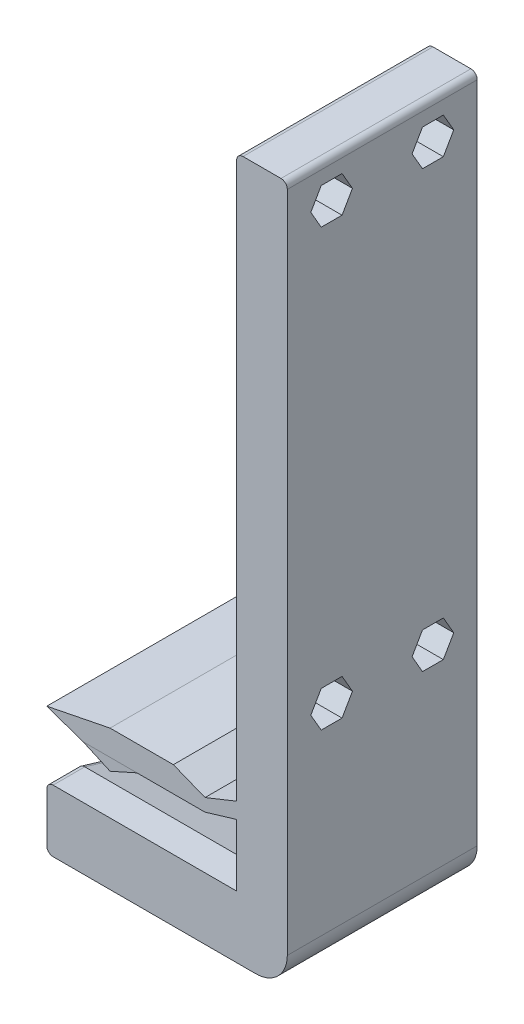
SolidWorks part; units mm, degrees
ref_plane "Front Plane" through (0, 0, 0) normal (0, 0, 1) x (1, 0, 0)
ref_plane "Top Plane" through (0, 0, 0) normal (0, 1, 0) x (1, 0, 0)
ref_plane "Right Plane" through (0, 0, 0) normal (1, 0, 0) x (0, 0, -1)
sketch "Sketch1" plane through (0, 0, 0) normal (0, 0, 1) x (1, 0, 0)
  line L0 (-13.25, 40.4) -> (-13.25, -40.4)
  line L1 (-13.25, 25.4) -> (13.25, 25.4)
  line L2 (-13.25, 25.4) -> (-13.25, -25.4)
  line L3 (-13.25, -25.4) -> (13.25, -25.4)
  line L4 (13.25, 25.4) -> (13.25, -25.4)
  line L5 (-13.25, 25.4) -> (13.25, -25.4) construction
  line L6 (-13.25, -25.4) -> (13.25, 25.4) construction
  line L7 (-13.25, 40.4) -> (-21.25, 40.4)
  line L8 (-21.25, 40.4) -> (-21.25, -40.4)
  line L9 (-21.25, -40.4) -> (-13.25, -40.4)
  point P0 (0, 0)
  point P9 (-13.25, 0)
  dimension "D1" = 26.5
  dimension "D2" = 50.8
  dimension "D3" = 15
  dimension "D4" = 8
extrude "Boss-Extrude1" add sketch "Sketch1" along normal blind 30 contours L8 L9 L0 L7
sketch "Sketch2" plane through (-13.25, 0, 0) normal (1, 0, 0) x (0, 0, -1)
  line L0 (-15, 40.4) -> (-15, -40.4) construction
  line L1 (-30, 40.4) -> (0, 40.4) construction
  line L2 (-30, -40.4) -> (0, -40.4) construction
  line L3 (0, 40.4) -> (0, -40.4) construction
  line L4 (-30, 25.4) -> (0, 25.4)
  line L5 (-30, 25.4) -> (-30, -25.4)
  line L6 (-30, -25.4) -> (0, -25.4)
  line L7 (0, 25.4) -> (0, -25.4)
  line L8 (-30, 25.4) -> (0, -25.4) construction
  line L9 (-30, -25.4) -> (0, 25.4) construction
  line L10 (-30, 40.4) -> (-30, -40.4) construction
  circle A0 centre (-7, 34.4) radius 1.65
  circle A1 centre (-23, 34.4) radius 1.65
  circle A2 centre (-23, -34.4) radius 1.65
  circle A3 centre (-7, -34.4) radius 1.65
  point P6 (-15, 0)
  dimension "D2" = 7
  dimension "D3" = 9
  dimension "D4" = 7
  dimension "D5" = 9
  dimension "D6" = 3.3
  dimension "D7" = 3.3
  dimension "D8" = 7
  dimension "D9" = 9
  dimension "D10" = 9
  dimension "D11" = 7
  dimension "D12" = 3.3
  dimension "D13" = 3.3
  dimension "D1" = 50.8
extrude "Cut-Extrude1" cut sketch "Sketch2" against normal blind 30 contours A1 | A0 | A2 | A3
sketch "Sketch3" plane through (-13.25, 0, 0) normal (1, 0, 0) x (0, 0, -1)
  line L0 (-30, -40.4) -> (0, -40.4) construction
  line L25 (-26.2909, 34.4) -> (-24.6454, 31.55)
  line L26 (-24.6454, 31.55) -> (-21.3546, 31.55)
  line L27 (-21.3546, 31.55) -> (-19.7091, 34.4)
  line L28 (-19.7091, 34.4) -> (-21.3546, 37.25)
  line L29 (-21.3546, 37.25) -> (-24.6454, 37.25)
  line L30 (-24.6454, 37.25) -> (-26.2909, 34.4)
  line L31 (-10.2909, 34.4) -> (-8.6454, 31.55)
  line L32 (-8.6454, 31.55) -> (-5.3546, 31.55)
  line L33 (-5.3546, 31.55) -> (-3.7091, 34.4)
  line L34 (-3.7091, 34.4) -> (-5.3546, 37.25)
  line L35 (-5.3546, 37.25) -> (-8.6454, 37.25)
  line L36 (-8.6454, 37.25) -> (-10.2909, 34.4)
  line L37 (-19.7091, -34.4) -> (-21.3546, -31.55)
  line L38 (-21.3546, -31.55) -> (-24.6454, -31.55)
  line L39 (-24.6454, -31.55) -> (-26.2909, -34.4)
  line L40 (-26.2909, -34.4) -> (-24.6454, -37.25)
  line L41 (-24.6454, -37.25) -> (-21.3546, -37.25)
  line L42 (-21.3546, -37.25) -> (-19.7091, -34.4)
  line L43 (-3.7091, -34.4) -> (-5.3546, -31.55)
  line L44 (-5.3546, -31.55) -> (-8.6454, -31.55)
  line L45 (-8.6454, -31.55) -> (-10.2909, -34.4)
  line L46 (-10.2909, -34.4) -> (-8.6454, -37.25)
  line L47 (-8.6454, -37.25) -> (-5.3546, -37.25)
  line L48 (-5.3546, -37.25) -> (-3.7091, -34.4)
  line L49 (-30, 40.4) -> (0, 40.4) construction
  circle A0 centre (-23, 34.4) radius 2.85 construction
  circle A1 centre (-7, 34.4) radius 2.85 construction
  circle A2 centre (-23, -34.4) radius 2.85 construction
  circle A3 centre (-7, -34.4) radius 2.85 construction
  point P28 (-23, -31.55)
  dimension "D1" = 5.7
  dimension "D2" = 5.7
  dimension "D3" = 5.7
  dimension "D4" = 5.7
  dimension "D5" = 180
  dimension "D6" = 0
  dimension "D7" = 0
  dimension "D8" = 0
extrude "Cut-Extrude3" cut sketch "Sketch3" along direction (1, 0, 0) on the side against the normal mid plane 10 contours L26 L27 L28 L29 L30 L25 | L32 L33 L34 L35 L36 L31 | L41 L42 L37 L38 L39 L40 | L44 L45 L46 L47 L48 L43
sketch "Sketch4" plane through (0, -40.4, 0) normal (0, -1, 0) x (1, 0, 0)
  line L1 (-21.25, 30) -> (-13.25, 30)
  line L2 (-21.25, 30) -> (-21.25, 0)
  line L3 (-21.25, 0) -> (-13.25, 0)
  line L4 (-13.25, 30) -> (-13.25, 0)
extrude "Boss-Extrude2" add sketch "Sketch4" along normal blind 30
sketch "Sketch5" plane through (-21.25, 0, 0) normal (-1, 0, 0) x (0, 0, 1)
  line L0 (30, 40.4) -> (30, -70.4) construction
  line L1 (0, -70.4) -> (30, -70.4)
  line L2 (0, -70.4) -> (0, -60.6)
  line L3 (0, -60.6) -> (30, -60.6)
  line L4 (30, -70.4) -> (30, -60.6)
  dimension "D1" = 9.8
extrude "Boss-Extrude3" add sketch "Sketch5" along normal blind 30
sketch "Sketch6" plane through (-21.25, 0, 0) normal (-1, 0, 0) x (0, 0, 1)
  line L0 (0, 40.4) -> (0, -60.6) construction
  line L1 (0, -48.3) -> (30, -48.3)
  line L2 (0, -48.3) -> (0, -52.3)
  line L3 (0, -52.3) -> (30, -52.3)
  line L4 (30, -48.3) -> (30, -52.3)
  line L5 (30, 40.4) -> (30, -60.6) construction
  line L6 (30, -60.6) -> (0, -60.6) construction
  dimension "D1" = 8.3
  dimension "D2" = 4
extrude "Boss-Extrude4" add sketch "Sketch6" along normal blind 30
sketch "Sketch8" plane through (0, 0, 0) normal (0, 0, -1) x (-1, 0, 0)
  line L0 (41.25, -52.3) -> (41.25, -54.2) construction
  line L1 (51.25, -52.3) -> (21.25, -52.3) construction
  line L2 (37, -52.3) -> (45.5, -52.3)
  line L3 (37, -52.3) -> (41.25, -54.2)
  line L4 (41.25, -54.2) -> (45.5, -52.3)
  line L5 (21.25, -52.3) -> (21.25, -60.6) construction
  point P7 (41.25, -52.3)
  dimension "D1" = 8.5
  dimension "D2" = 1.9
  dimension "D3" = 20
extrude "Boss-Extrude5" add sketch "Sketch8" against normal blind 30 separate body
sketch "Sketch9" plane through (0, 0, 0) normal (0, 0, -1) x (-1, 0, 0)
  line L0 (51.25, -52.3) -> (51.25, -50.3) construction
  line L1 (51.25, -48.3) -> (51.25, -52.3) construction
  line L2 (41.25, -54.2) -> (41.25, -48.3) construction
  line L3 (51.25, -48.3) -> (21.25, -48.3) construction
  line L4 (41.25, -48.3) -> (51.25, -50.3) construction
  line L5 (51.25, -50.3) -> (45.5, -52.3) construction
  line L6 (41.25, -48.3) -> (51.25, -50.3)
  line L7 (51.25, -50.3) -> (45.5, -52.3)
  line L8 (21.25, -48.3) -> (31.25, -48.3)
  line L9 (26.25, -48.3) -> (26.25, -50.3) construction
  line L10 (26.25, -50.3) -> (31.25, -48.3)
  line L11 (26.25, -50.3) -> (21.25, -48.3)
  line L12 (37, -52.3) -> (45.5, -52.3)
  line L13 (21.25, 40.4) -> (21.25, -48.3) construction
  line L14 (41.25, -48.3) -> (51.25, -48.3)
  line L15 (51.25, -48.3) -> (51.25, -50.3)
  line L16 (51.25, -52.3) -> (45.5, -52.3)
  line L17 (45.5, -52.3) -> (51.25, -52.3)
  line L18 (51.25, -50.3) -> (45.5, -52.3)
  line L19 (45.5, -52.3) -> (51.25, -52.3)
  line L20 (51.25, -52.3) -> (51.25, -50.3)
  line L21 (45.5, -52.3) -> (51.25, -50.3)
  point P16 (26.25, -48.3)
  line M14 (51.25, -52.3) -> (51.25, -48.3)
  line M15 (51.25, -48.3) -> (21.25, -48.3)
  dimension "D1" = 10
  dimension "D2" = 5
  dimension "D3" = 2
extrude "Cut-Extrude8" cut sketch "Sketch9" against normal blind 30 contours L6 M15 M14 | L11 L10 M15
sketch "Sketch10" plane through (-51.25, 0, 0) normal (-1, 0, 0) x (0, 0, 1)
  line L0 (5, -60.6) -> (25, -60.6)
  line L2 (30, -60.6) -> (0, -60.6) construction
  line L3 (15, -60.6) -> (15, -63.6) construction
  line L4 (5, -60.6) -> (15, -63.6)
  line L5 (15, -63.6) -> (25, -60.6)
  line L6 (0, -60.6) -> (0, -70.4) construction
  point P5 (7.2012, -60.4)
  point P6 (15, -60.6)
  dimension "D1" = 3
  dimension "D2" = 20
  dimension "D3" = 15
extrude "Cut-Extrude9" cut sketch "Sketch10" against normal blind 30
sketch "Sketch11" plane through (0, 0, 0) normal (0, 0, -1) x (-1, 0, 0)
  line L0 (21.25, -48.3) -> (21.25, -52.3) construction
  line L1 (26.25, -50.3) -> (26.25, -52.3) construction
  line L3 (51.25, -52.3) -> (21.25, -52.3) construction
  line L4 (31.25, -48.3) -> (31.25, -52.3) construction
  line L5 (45.5, -52.3) -> (51.25, -50.3)
  line L6 (51.25, -50.3) -> (51.25, -52.3)
  line L7 (51.25, -52.3) -> (45.5, -52.3)
  line L8 (21.25, -52.3) -> (21.25, -50.8)
  line L9 (21.25, -50.8) -> (26.25, -52.3)
  line L10 (21.25, -52.3) -> (26.25, -52.3)
  dimension "D1" = 2.5
extrude "Cut-Extrude10" cut sketch "Sketch11" against normal blind 30
fillet "Fillet1" radius 1 5 edges at (-51.25, -60.6, 27.5) (-51.25, -62.1, 20) (-51.25, -62.1, 10) (-51.25, -60.6, 2.5) (-51.25, -70.4, 15)
fillet "Fillet2" radius 5 1 edges at (-13.25, -70.4, 15)
fillet "Fillet3" radius 1 2 edges at (-13.25, 40.4, 15) (-21.25, 40.4, 15)
